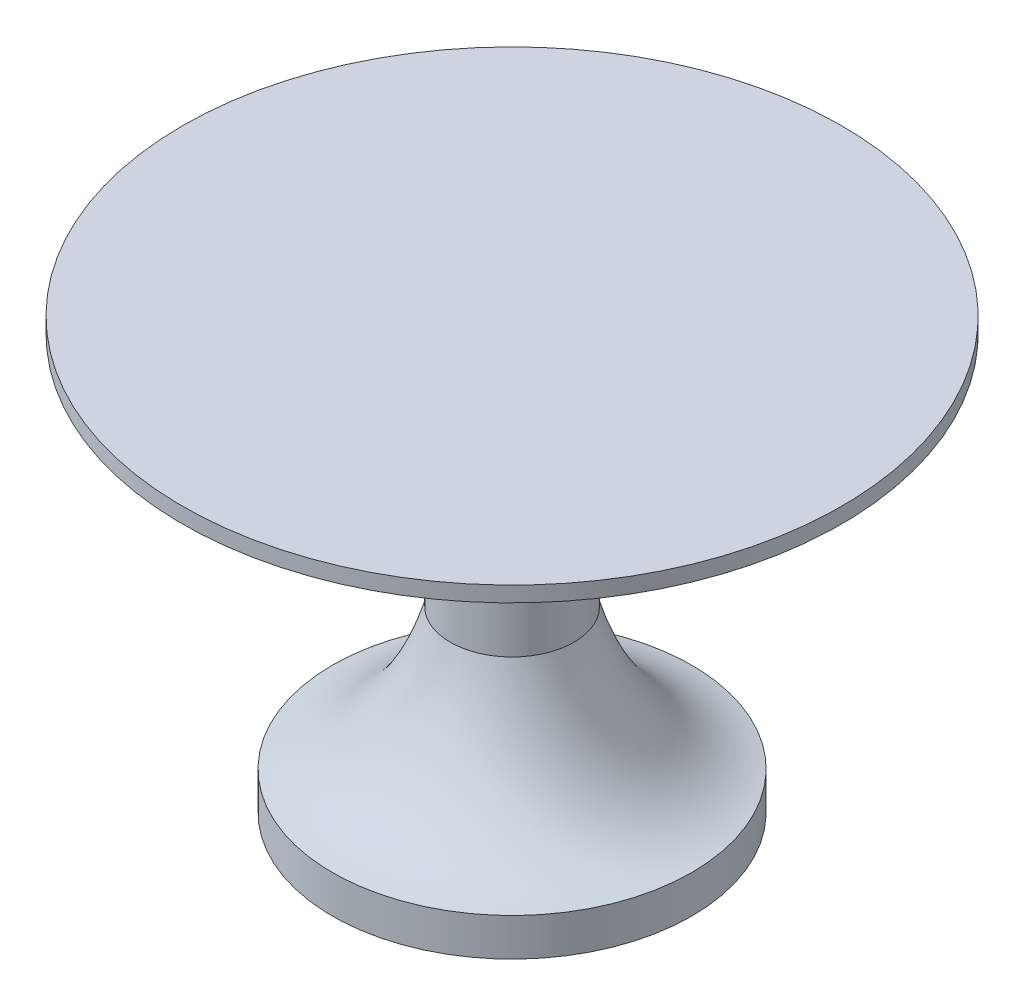
SolidWorks part; units mm, degrees
ref_plane "Front Plane" through (0, 0, 0) normal (0, 0, 1) x (1, 0, 0)
ref_plane "Top Plane" through (0, 0, 0) normal (0, 1, 0) x (1, 0, 0)
ref_plane "Right Plane" through (0, 0, 0) normal (1, 0, 0) x (0, 0, -1)
sketch "Sketch2" plane through (0, 0, 0) normal (0, 0, 1) x (1, 0, 0)
  line L0 (0, 0) -> (0, 28.575)
  line L1 (0, 28.575) -> (609.6, 28.575)
  line L2 (609.6, 28.575) -> (609.6, 0)
  line L3 (0, 0) -> (609.6, 0)
  line L4 (0, 0) -> (0, -508)
  line L5 (0, -508) -> (114.3904, -508)
  line L6 (114.3904, -508) -> (114.3904, 0)
  line L7 (0, 28.575) -> (0, -508)
  line L8 (609.6, 28.575) -> (609.6, 14.2875)
  line L9 (332.3165, -696.8533) -> (332.3165, -766.7033)
  line L10 (0, 0) -> (114.3904, 0)
  spline S0 degree 3 poles (114.3904, -436.8569) (144.8848, -546.8185) (207.1017, -672.8163) (332.3165, -696.8533) knots 0 0 0 0 1 1 1 1
  spline S1 degree 3 poles (332.3165, -766.7033) (180.7878, -766.2277) (148.1045, -589.3571) (57.1952, -508) knots 0 0 0 0 1 1 1 1
  dimension "D1" = 28.575
  dimension "D2" = 609.6
  dimension "D3" = 28.575
  dimension "D4" = 508
revolve "Revolve1" add sketch "Sketch2" angle 360 about L4
